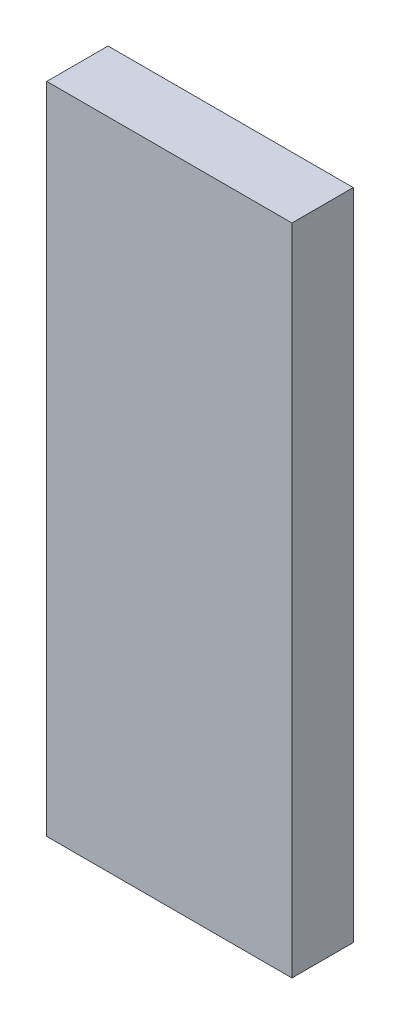
SolidWorks part; units mm, degrees
ref_plane "Front Plane" through (0, 0, 0) normal (0, 0, 1) x (1, 0, 0)
ref_plane "Top Plane" through (0, 0, 0) normal (0, 1, 0) x (1, 0, 0)
ref_plane "Right Plane" through (0, 0, 0) normal (1, 0, 0) x (0, 0, -1)
sketch "Sketch1" plane through (0, 0, 0) normal (0, 0, 1) x (1, 0, 0)
  line L0 (68.5859, -160) -> (68.5859, -200) construction
  line L1 (62.5859, -164) -> (74.5859, -164)
  line L2 (62.5859, -164) -> (62.5859, -196)
  line L3 (62.5859, -196) -> (74.5859, -196)
  line L4 (74.5859, -164) -> (74.5859, -196)
  dimension "D1" = 6
  dimension "D2" = 12
extrude "Boss-Extrude1" add sketch "Sketch1" along normal blind 3
